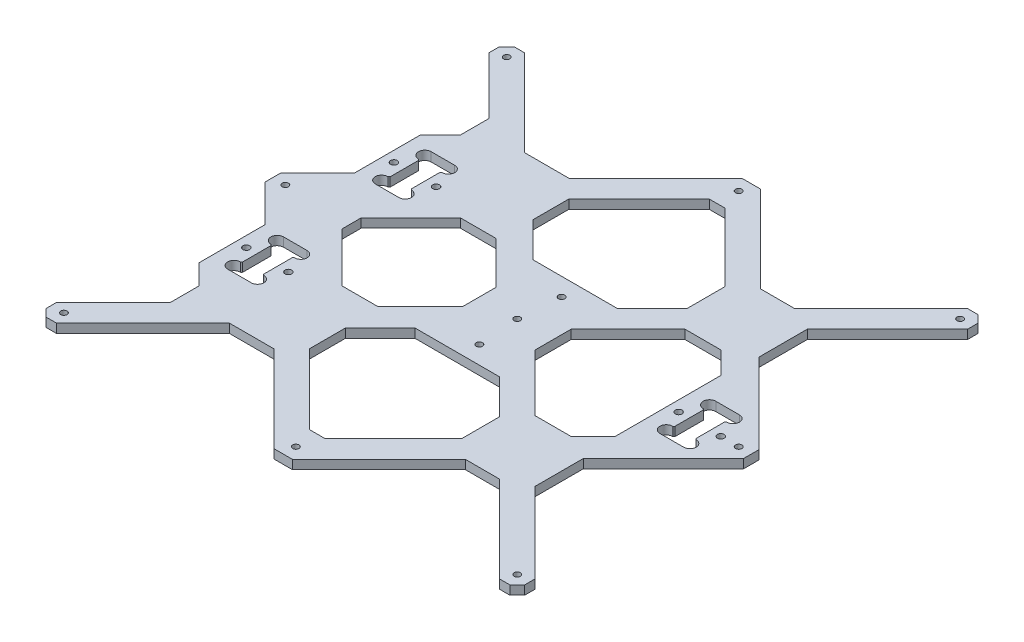
SolidWorks part; units mm, degrees
material "6063-O, Extruded Rod (SS)"
ref_plane "Front Plane" through (0, 0, 0) normal (0, 0, 1) x (1, 0, 0)
ref_plane "Top Plane" through (0, 0, 0) normal (0, 1, 0) x (1, 0, 0)
ref_plane "Right Plane" through (0, 0, 0) normal (1, 0, 0) x (0, 0, -1)
sketch "Sketch2" plane through (0, 0, 0) normal (0, 1, 0) x (1, 0, 0)
  line L0 (162, 177.023) -> (141.977, 157)
  line L1 (141.977, 157) -> (125, 157)
  line L2 (125, 157) -> (101.5, 180.5)
  line L3 (101.5, 189.5) -> (125, 213)
  line L4 (125, 213) -> (141.977, 213)
  line L5 (141.977, 213) -> (162, 192.977)
  line L6 (251.5, 210.0147) -> (240.9853, 220.5294)
  line L7 (240.9853, 220.5294) -> (224.0147, 220.5294)
  line L8 (224.0147, 220.5294) -> (197, 193.5147)
  line L9 (197, 176.4853) -> (224.0147, 149.4706)
  line L10 (224.0147, 149.4706) -> (240.9853, 149.4706)
  line L11 (240.9853, 149.4706) -> (251.5, 159.9853)
  line L12 (184.4001, 296) -> (225.4001, 255)
  line L13 (225.4001, 255) -> (241.5147, 255)
  line L14 (241.5147, 255) -> (282.5147, 296)
  line L15 (282.5147, 296) -> (287.4852, 296)
  line L16 (287.4852, 296) -> (291, 292.4852)
  line L17 (291, 292.4852) -> (291, 287.5147)
  line L18 (291, 287.5147) -> (253, 249.5147)
  line L19 (253, 249.5147) -> (253, 226.667)
  line L20 (253, 226.667) -> (291, 188.667)
  line L21 (291, 188.667) -> (291, 181.333)
  line L22 (291, 181.333) -> (253, 143.333)
  line L23 (253, 143.333) -> (253, 120.4853)
  line L24 (253, 120.4853) -> (291, 82.4853)
  line L25 (291, 82.4853) -> (291, 77.5148)
  line L26 (291, 77.5148) -> (287.4852, 74)
  line L27 (287.4852, 74) -> (282.5147, 74)
  line L28 (282.5147, 74) -> (241.5147, 115)
  line L29 (241.5147, 115) -> (225.4001, 115)
  line L30 (225.4001, 115) -> (184.4001, 74)
  line L31 (184.4001, 74) -> (175.5999, 74)
  line L32 (175.5999, 74) -> (134.5999, 115)
  line L33 (134.5999, 115) -> (113.4853, 115)
  line L34 (113.4853, 115) -> (72.4853, 74)
  line L35 (72.4853, 74) -> (67.5148, 74)
  line L36 (67.5148, 74) -> (64, 77.5148)
  line L37 (64, 77.5148) -> (64, 82.4853)
  line L38 (64, 82.4853) -> (91, 109.4853)
  line L39 (91, 109.4853) -> (91, 123)
  line L40 (91, 123) -> (81.5, 132.5)
  line L41 (81.5, 132.5) -> (81.5, 163.7609)
  line L42 (81.5, 163.7609) -> (64, 181.2609)
  line L43 (64, 188.7391) -> (81.5, 206.2391)
  line L44 (81.5, 206.2391) -> (81.5, 237.5)
  line L45 (81.5, 237.5) -> (91, 247)
  line L46 (91, 247) -> (91, 260.5147)
  line L47 (91, 260.5147) -> (64, 287.5147)
  line L48 (64, 287.5147) -> (64, 292.4852)
  line L49 (64, 292.4852) -> (67.5148, 296)
  line L50 (67.5148, 296) -> (72.4853, 296)
  line L51 (72.4853, 296) -> (113.4853, 255)
  line L52 (113.4853, 255) -> (134.5999, 255)
  line L53 (134.5999, 255) -> (175.5999, 296)
  line L54 (175.5999, 296) -> (184.4001, 296)
  line L55 (143, 246.4158) -> (143, 229.5663)
  line L56 (143, 229.5663) -> (159.5663, 213)
  line L57 (159.5663, 213) -> (199.5147, 213)
  line L58 (199.5147, 213) -> (216, 229.4853)
  line L59 (216, 229.4853) -> (216, 247.4296)
  line L60 (216, 247.4296) -> (183.6826, 279.747)
  line L61 (183.6826, 279.747) -> (176.3174, 279.7332)
  line L62 (176.3174, 279.7332) -> (143, 246.4158)
  line L63 (143, 123.5842) -> (143, 140.4337)
  line L64 (143, 140.4337) -> (159.5663, 157)
  line L65 (159.5663, 157) -> (199.5147, 157)
  line L66 (199.5147, 157) -> (216, 140.5147)
  line L67 (216, 140.5147) -> (216, 122.5704)
  line L68 (216, 122.5704) -> (183.6826, 90.253)
  line L69 (183.6826, 90.253) -> (176.3174, 90.2668)
  line L70 (176.3174, 90.2668) -> (143, 123.5842)
  line L71 (101.5, 226.75) -> (101.5, 213.25)
  line L72 (271.5, 191.75) -> (271.5, 178.25)
  line L73 (101.5, 156.75) -> (101.5, 143.25)
  line L74 (91.5, 226.75) -> (91.5, 213.25)
  line L75 (261.5, 191.75) -> (261.5, 178.25)
  line L76 (91.5, 156.75) -> (91.5, 143.25)
  line L77 (93.6792, 358.4107) -> (93.6792, 347.8262)
  line L78 (93.6792, 347.8262) -> (93.9406, 345.7354)
  line L79 (93.9406, 345.7354) -> (94.4633, 344.2327)
  line L80 (94.4633, 344.2327) -> (95.182, 343.1873)
  line L81 (95.182, 343.1873) -> (96.1846, 341.9648)
  line L82 (96.1846, 341.9648) -> (97.8105, 341.4329)
  line L83 (97.8105, 341.4329) -> (99.6248, 341.0966)
  line L84 (99.6248, 341.0966) -> (101.977, 341.3579)
  line L85 (101.977, 341.3579) -> (104.0024, 342.4033)
  line L86 (104.0024, 342.4033) -> (105.1131, 344.2327)
  line L87 (105.1131, 344.2327) -> (105.5705, 346.7155)
  line L88 (105.5705, 346.7155) -> (105.5705, 349.1983)
  line L89 (105.5705, 349.1983) -> (105.5705, 358.4107)
  line L90 (79.8932, 349.3289) -> (80.0892, 349.3289)
  line L91 (80.0892, 349.3289) -> (81.0039, 348.8063)
  line L92 (81.0039, 348.8063) -> (82.0493, 347.4342)
  line L93 (82.0493, 347.4342) -> (86.4922, 341.0966)
  line L94 (73.5556, 341.1619) -> (73.5556, 358.4107)
  line L95 (73.5556, 358.4107) -> (80.6119, 358.4107)
  line L96 (80.6119, 358.4107) -> (82.768, 357.7574)
  line L97 (82.768, 357.7574) -> (83.8134, 356.7773)
  line L98 (83.8134, 356.7773) -> (84.5321, 355.4706)
  line L99 (84.5321, 355.4706) -> (84.8588, 353.7065)
  line L100 (84.8588, 353.7065) -> (84.5321, 352.0078)
  line L101 (84.5321, 352.0078) -> (83.6827, 350.5703)
  line L102 (83.6827, 350.5703) -> (82.5067, 349.8517)
  line L103 (82.5067, 349.8517) -> (81.3306, 349.525)
  line L104 (81.3306, 349.525) -> (79.8932, 349.3289)
  line L105 (79.8932, 349.3289) -> (78.1291, 349.3289)
  line L106 (78.1291, 349.3289) -> (73.5556, 349.3289)
  line L107 (113.0897, 345.4442) -> (114.2004, 343.4842)
  line L108 (114.2004, 343.4842) -> (116.6178, 341.8507)
  line L109 (116.6178, 341.8507) -> (118.9699, 341.1974)
  line L110 (118.9699, 341.1974) -> (122.4328, 341.7201)
  line L111 (122.4328, 341.7201) -> (124.0662, 343.0268)
  line L112 (124.0662, 343.0268) -> (125.2422, 345.1176)
  line L113 (125.2422, 345.1176) -> (125.2422, 346.359)
  line L114 (125.2422, 346.359) -> (124.9156, 347.4697)
  line L115 (124.9156, 347.4697) -> (123.7395, 348.7764)
  line L116 (123.7395, 348.7764) -> (122.5635, 349.2991)
  line L117 (122.5635, 349.2991) -> (116.7485, 351.0632)
  line L118 (116.7485, 351.0632) -> (115.0497, 352.1739)
  line L119 (115.0497, 352.1739) -> (114.0044, 353.4153)
  line L120 (114.0044, 353.4153) -> (113.8737, 354.5914)
  line L121 (113.8737, 354.5914) -> (114.135, 356.3554)
  line L122 (114.135, 356.3554) -> (115.3764, 357.6622)
  line L123 (115.3764, 357.6622) -> (117.4672, 358.4462)
  line L124 (117.4672, 358.4462) -> (120.0807, 358.5769)
  line L125 (120.0807, 358.5769) -> (122.8248, 357.8582)
  line L126 (122.8248, 357.8582) -> (123.9355, 356.8128)
  line L127 (123.9355, 356.8128) -> (124.3929, 355.5714)
  line L128 (130.9954, 341.0312) -> (137.9864, 358.5414)
  line L129 (137.9864, 358.5414) -> (139.0972, 358.5414)
  line L130 (139.0972, 358.5414) -> (145.9575, 341.0312)
  line L131 (143.9343, 346.1951) -> (133.0803, 346.1927)
  line L132 (55, 341.1619) -> (55, 358.4107)
  line L133 (55, 358.4107) -> (62.0563, 358.4107)
  line L134 (62.0563, 358.4107) -> (64.2125, 357.7574)
  line L135 (64.2125, 357.7574) -> (65.2578, 356.7773)
  line L136 (65.2578, 356.7773) -> (65.9765, 355.4706)
  line L137 (65.9765, 355.4706) -> (66.3032, 353.7065)
  line L138 (66.3032, 353.7065) -> (65.9765, 352.0078)
  line L139 (65.9765, 352.0078) -> (65.1272, 350.5703)
  line L140 (65.1272, 350.5703) -> (63.9511, 349.8517)
  line L141 (63.9511, 349.8517) -> (62.7751, 349.525)
  line L142 (62.7751, 349.525) -> (61.3376, 349.3289)
  line L143 (61.3376, 349.3289) -> (59.5735, 349.3289)
  line L144 (59.5735, 349.3289) -> (55, 349.3289)
  line L145 (251.5, 210.0147) -> (251.5, 159.9853)
  line L146 (197, 193.5147) -> (197, 176.4853)
  line L147 (64, 188.7391) -> (64, 181.2609)
  line L148 (101.5, 189.5) -> (101.5, 180.5)
  line L149 (162, 192.977) -> (162, 177.023)
  line L150 (102.1, 142.75) -> (102, 142.75)
  line L151 (272.1, 177.75) -> (272, 177.75)
  line L152 (102.1, 212.75) -> (102, 212.75)
  line L153 (90.9, 142.75) -> (91, 142.75)
  line L154 (260.9, 177.75) -> (261, 177.75)
  line L155 (90.9, 212.75) -> (91, 212.75)
  line L156 (102, 142.75) -> (101.5, 143.25)
  line L157 (272, 177.75) -> (271.5, 178.25)
  line L158 (102, 212.75) -> (101.5, 213.25)
  line L159 (91, 142.75) -> (91.5, 143.25)
  line L160 (261, 177.75) -> (261.5, 178.25)
  line L161 (91, 212.75) -> (91.5, 213.25)
  line L162 (102.1, 157.25) -> (102, 157.25)
  line L163 (272.1, 192.25) -> (272, 192.25)
  line L164 (102.1, 227.25) -> (102, 227.25)
  line L165 (90.9, 157.25) -> (91, 157.25)
  line L166 (260.9, 192.25) -> (261, 192.25)
  line L167 (90.9, 227.25) -> (91, 227.25)
  line L168 (101.5, 156.75) -> (102, 157.25)
  line L169 (271.5, 191.75) -> (272, 192.25)
  line L170 (101.5, 226.75) -> (102, 227.25)
  line L171 (91.5, 156.75) -> (91, 157.25)
  line L172 (261.5, 191.75) -> (261, 192.25)
  line L173 (91.5, 226.75) -> (91, 227.25)
  line L174 (90.9, 163.25) -> (102.1, 163.25)
  line L175 (260.9, 198.25) -> (272.1, 198.25)
  line L176 (90.9, 233.25) -> (102.1, 233.25)
  line L177 (90.9, 136.75) -> (102.1, 136.75)
  line L178 (260.9, 171.75) -> (272.1, 171.75)
  line L179 (90.9, 206.75) -> (102.1, 206.75)
  arc A0 (102.1, 206.75) -> (102.1, 212.75) centre (102.1, 209.75) ccw
  arc A1 (272.1, 171.75) -> (272.1, 177.75) centre (272.1, 174.75) ccw
  arc A2 (102.1, 136.75) -> (102.1, 142.75) centre (102.1, 139.75) ccw
  arc A3 (90.9, 142.75) -> (90.9, 136.75) centre (90.9, 139.75) ccw
  arc A4 (90.9, 212.75) -> (90.9, 206.75) centre (90.9, 209.75) ccw
  arc A5 (260.9, 177.75) -> (260.9, 171.75) centre (260.9, 174.75) ccw
  arc A6 (102.1, 157.25) -> (102.1, 163.25) centre (102.1, 160.25) ccw
  arc A7 (102.1, 227.25) -> (102.1, 233.25) centre (102.1, 230.25) ccw
  arc A8 (272.1, 192.25) -> (272.1, 198.25) centre (272.1, 195.25) ccw
  arc A9 (90.9, 163.25) -> (90.9, 157.25) centre (90.9, 160.25) ccw
  arc A10 (260.9, 198.25) -> (260.9, 192.25) centre (260.9, 195.25) ccw
  arc A11 (90.9, 233.25) -> (90.9, 227.25) centre (90.9, 230.25) ccw
  circle A12 centre (318.6, 4.9) radius 2.55
  circle A13 centre (318.6, 28.1) radius 2.55
  circle A14 centre (295.4, 28.1) radius 2.55
  circle A15 centre (295.4, 4.9) radius 2.55
  circle A16 centre (281.6, 4.9) radius 2.55
  circle A17 centre (258.4, 4.9) radius 2.55
  circle A18 centre (258.4, 28.1) radius 2.55
  circle A19 centre (281.6, 28.1) radius 2.55
  circle A20 centre (111.6, 4.9) radius 2.55
  circle A21 centre (111.6, 28.1) radius 2.55
  circle A22 centre (88.4, 28.1) radius 2.55
  circle A23 centre (88.4, 4.9) radius 2.55
  circle A24 centre (74.6, 4.9) radius 2.55
  circle A25 centre (74.6, 28.1) radius 2.55
  circle A26 centre (51.4, 28.1) radius 2.55
  circle A27 centre (51.4, 4.9) radius 2.55
  circle A28 centre (360, 39.8) radius 1.5
  circle A29 centre (10, 39.8) radius 1.5
  circle A30 centre (340, 359.8) radius 1.5
  circle A31 centre (30, 39.8) radius 1.5
  circle A32 centre (42.9, 67.8) radius 1.5
  circle A33 centre (340, 39.8) radius 1.5
  circle A34 centre (10, 359.8) radius 1.5
  circle A35 centre (350, 19.8) radius 1.5
  circle A36 centre (47, 99.8) radius 1.5
  circle A37 centre (3.7, 181.1) radius 1.5
  circle A38 centre (20, 19.8) radius 1.5
  circle A39 centre (4.9, 67.8) radius 1.5
  circle A40 centre (360, 359.8) radius 1.5
  circle A41 centre (42.9, 161.8) radius 1.5
  circle A42 centre (3.7, 99.8) radius 1.5
  circle A43 centre (30, 359.8) radius 1.5
  circle A44 centre (47, 174.7) radius 1.5
  circle A45 centre (4.9, 161.8) radius 1.5
  circle A46 centre (46.5, 269.3) radius 1.5
  circle A47 centre (15, 247.8) radius 1.5
  circle A48 centre (3.5, 269.3) radius 1.5
  circle A49 centre (15, 290.8) radius 1.5
  circle A50 centre (180, 80) radius 1.5
  circle A51 centre (180, 290) radius 1.5
  circle A52 centre (285, 80) radius 1.5
  circle A53 centre (70, 290) radius 1.5
  circle A54 centre (285, 290) radius 1.5
  circle A55 centre (70, 185) radius 1.5
  circle A56 centre (180, 185) radius 1.5
  circle A57 centre (285, 185) radius 1.5
  circle A58 centre (256.5, 185) radius 1.6
  circle A59 centre (276.5, 185) radius 1.6
  circle A60 centre (106.5, 220) radius 1.6
  circle A61 centre (106.5, 150) radius 1.6
  circle A62 centre (86.5, 220) radius 1.6
  circle A63 centre (86.5, 150) radius 1.6
  circle A64 centre (70, 80) radius 1.5
  circle A65 centre (181.5, 165.5) radius 1.5
  circle A66 centre (181.5, 204.5) radius 1.5
  circle A67 centre (40, 7) radius 1.6
  circle A68 centre (331, 7) radius 1.6
  circle A69 centre (343, 7) radius 1.6
  circle A70 centre (120, 13) radius 1.6
  circle A71 centre (120, 4) radius 1.6
  circle A72 centre (230, 13) radius 1.6
  circle A73 centre (230, 4) radius 1.6
  circle A74 centre (333.4, 205) radius 2.1
  circle A75 centre (333.4, 88) radius 2.1
  circle A76 centre (26, 7) radius 1.6
  circle A77 centre (153, 13) radius 1.6
  circle A78 centre (153, 4) radius 1.6
  spline S0 degree 2 poles (5, 370) (2.5, 367.5) (0, 365) knots 1472.868668 1472.868668 1472.868668 1479.939736 1479.939736 1479.939736
  spline S1 degree 2 poles (365, 370) (185, 370) (5, 370) knots 1112.868668 1112.868668 1112.868668 1472.868668 1472.868668 1472.868668
  spline S2 degree 2 poles (370, 365) (367.5, 367.5) (365, 370) knots 1105.7976 1105.7976 1105.7976 1112.868668 1112.868668 1112.868668
  spline S3 degree 2 poles (370, 5) (370, 185) (370, 365) knots 745.7976 745.7976 745.7976 1105.7976 1105.7976 1105.7976
  spline S4 degree 2 poles (365, 0) (367.5, 2.5) (370, 5) knots 738.726533 738.726533 738.726533 745.7976 745.7976 745.7976
  spline S5 degree 2 poles (345, 0) (355, 0) (365, 0) knots 718.726533 718.726533 718.726533 738.726533 738.726533 738.726533
  spline S6 degree 2 poles (341, 4) (343, 2) (345, 0) knots 710.241251 710.241251 710.241251 718.726533 718.726533 718.726533
  spline S7 degree 2 poles (333, 4) (337, 4) (341, 4) knots 704.241251 704.241251 704.241251 710.241251 710.241251 710.241251
  spline S8 degree 2 poles (329, 0) (331, 2) (333, 4) knots 698.584397 698.584397 698.584397 704.241251 704.241251 704.241251
  spline S9 degree 2 poles (151, 0) (240, 0) (329, 0) knots 507.584397 507.584397 507.584397 698.584397 698.584397 698.584397
  spline S10 degree 2 poles (146, 5) (148.5, 2.5) (151, 0) knots 501.927543 501.927543 501.927543 507.584397 507.584397 507.584397
  spline S11 degree 2 poles (127, 5) (136.5, 5) (146, 5) knots 487.927543 487.927543 487.927543 501.927543 501.927543 501.927543
  spline S12 degree 2 poles (122, 0) (124.5, 2.5) (127, 5) knots 482.270688 482.270688 482.270688 487.927543 487.927543 487.927543
  spline S13 degree 2 poles (41, 0) (81.5, 0) (122, 0) knots 407.270688 407.270688 407.270688 482.270688 482.270688 482.270688
  spline S14 degree 2 poles (37, 4) (39, 2) (41, 0) knots 401.613834 401.613834 401.613834 407.270688 407.270688 407.270688
  spline S15 degree 2 poles (29, 4) (33, 4) (37, 4) knots 395.613834 395.613834 395.613834 401.613834 401.613834 401.613834
  spline S16 degree 2 poles (25, 0) (27, 2) (29, 4) knots 387.128553 387.128553 387.128553 395.613834 395.613834 395.613834
  spline S17 degree 2 poles (5, 0) (15, 0) (25, 0) knots 367.128553 367.128553 367.128553 387.128553 387.128553 387.128553
  spline S18 degree 2 poles (0, 5) (2.5, 2.5) (5, 0) knots 360.191742 360.191742 360.191742 367.128553 367.128553 367.128553
  spline S19 degree 2 poles (0, 365) (0, 185) (0, 5) knots 0 0 0 360.191742 360.191742 360.191742
  spline S20 degree 2 poles (93, 31.5) (100, 31.5) (107, 31.5) knots 1110.421356 1110.421356 1110.421356 1117.046356 1117.046356 1117.046356
  spline S21 degree 2 poles (88, 36.5) (90.5, 34) (93, 31.5) knots 1103.350288 1103.350288 1103.350288 1110.421356 1110.421356 1110.421356
  spline S22 degree 2 poles (83, 36.5) (85.5, 36.5) (88, 36.5) knots 1098.350288 1098.350288 1098.350288 1103.350288 1103.350288 1103.350288
  spline S23 degree 2 poles (73, 46.5) (78, 41.5) (83, 36.5) knots 1084.208153 1084.208153 1084.208153 1098.350288 1098.350288 1098.350288
  spline S24 degree 2 poles (55, 46.5) (64, 46.5) (73, 46.5) knots 1066.208153 1066.208153 1066.208153 1084.208153 1084.208153 1084.208153
  spline S25 degree 2 poles (50, 51.5) (52.5, 49) (55, 46.5) knots 1059.137085 1059.137085 1059.137085 1066.208153 1066.208153 1066.208153
  spline S26 degree 2 poles (50, 325) (50, 188.25) (50, 51.5) knots 787.637085 787.637085 787.637085 1059.137085 1059.137085 1059.137085
  spline S27 degree 2 poles (55, 330) (52.5, 327.5) (50, 325) knots 780.566017 780.566017 780.566017 787.637085 787.637085 787.637085
  spline S28 degree 2 poles (315, 330) (185, 330) (55, 330) knots 520.566017 520.566017 520.566017 780.566017 780.566017 780.566017
  spline S29 degree 2 poles (320, 325) (317.5, 327.5) (315, 330) knots 513.494949 513.494949 513.494949 520.566017 520.566017 520.566017
  spline S30 degree 2 poles (320, 51.5) (320, 188.25) (320, 325) knots 241.994949 241.994949 241.994949 513.494949 513.494949 513.494949
  spline S31 degree 2 poles (315, 46.5) (317.5, 49) (320, 51.5) knots 234.923882 234.923882 234.923882 241.994949 241.994949 241.994949
  spline S32 degree 2 poles (297, 46.5) (306, 46.5) (315, 46.5) knots 216.923882 216.923882 216.923882 234.923882 234.923882 234.923882
  spline S33 degree 2 poles (287, 36.5) (292, 41.5) (297, 46.5) knots 202.781746 202.781746 202.781746 216.923882 216.923882 216.923882
  spline S34 degree 2 poles (282, 36.5) (284.5, 36.5) (287, 36.5) knots 197.781746 197.781746 197.781746 202.781746 202.781746 202.781746
  spline S35 degree 2 poles (277, 31.5) (279.5, 34) (282, 36.5) knots 190.710678 190.710678 190.710678 197.781746 197.781746 197.781746
  spline S36 degree 2 poles (263, 31.5) (264, 31.5) (265, 31.5) (270, 31.5) (275, 31.5) (276, 31.5) (277, 31.5) knots 176.710678 176.710678 176.710678 178.710678 178.710678 188.710678 188.710678 190.710678 190.710678 190.710678
  spline S37 degree 2 poles (258, 36.5) (260.5, 34) (263, 31.5) knots 169.63961 169.63961 169.63961 176.710678 176.710678 176.710678
  spline S38 degree 2 poles (210, 36.5) (211.75, 36.5) (213.5, 36.5) (235.75, 36.5) (258, 36.5) knots 121.63961 121.63961 121.63961 125.13961 125.13961 169.63961 169.63961 169.63961
  spline S39 degree 2 poles (190, 16.5) (200, 26.5) (210, 36.5) knots 93.355339 93.355339 93.355339 121.63961 121.63961 121.63961
  spline S40 degree 2 poles (180, 16.5) (185, 16.5) (190, 16.5) knots 83.355339 83.355339 83.355339 93.355339 93.355339 93.355339
  spline S41 degree 2 poles (160, 36.5) (170, 26.5) (180, 16.5) knots 55.071068 55.071068 55.071068 83.355339 83.355339 83.355339
  spline S42 degree 2 poles (112, 36.5) (134.25, 36.5) (156.5, 36.5) (158.25, 36.5) (160, 36.5) knots 7.071068 7.071068 7.071068 51.571068 51.571068 55.071068 55.071068 55.071068
  spline S43 degree 2 poles (107, 31.5) (109.5, 34) (112, 36.5) knots 0 0 0 7.071068 7.071068 7.071068
extrude "Boss-Extrude2" add sketch "Sketch2" along normal blind 4.25 contours L43 L147 L42 L41 L40 L39 L38 L37 L36 L35 L34 L33 L32 L31 L30 L29 L28 L27 L26 L25 L24 L23 L22 L21 L20 L19 L18 L17 L16 L15 L14 L13 L12 L54 L53 L52 L51 L50 L49 L48 L47 L46 L45 L44 A66 A65 A64
